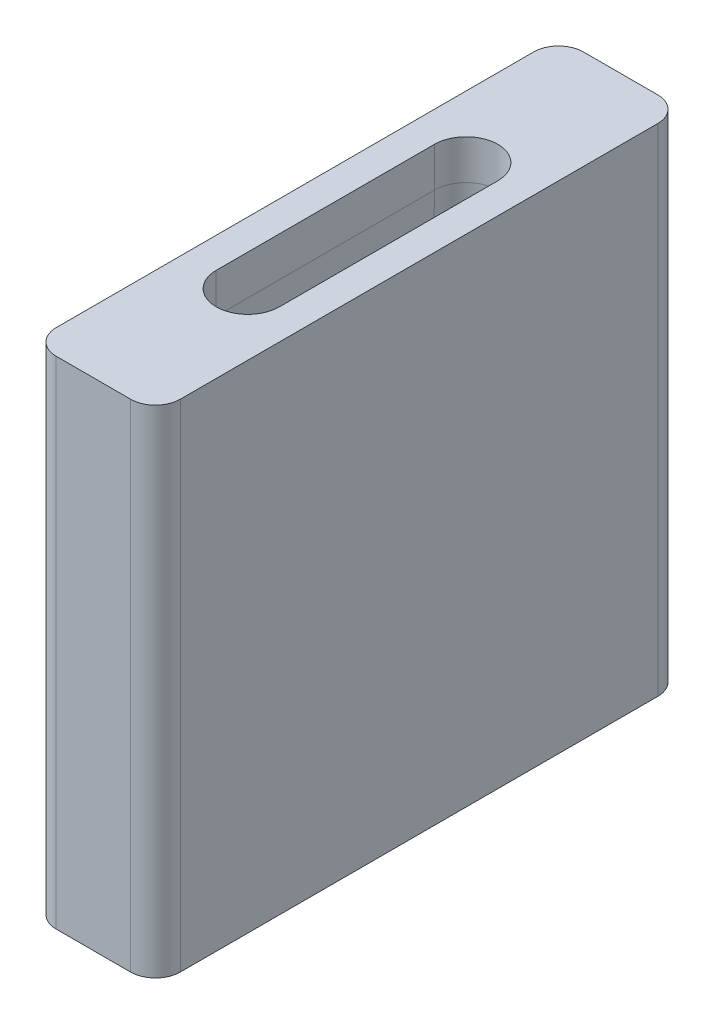
SolidWorks part; units mm, degrees
material "K110"
ref_plane "Front Plane" through (0, 0, 0) normal (0, 0, 1) x (1, 0, 0)
ref_plane "Top Plane" through (0, 0, 0) normal (0, 1, 0) x (1, 0, 0)
ref_plane "Right Plane" through (0, 0, 0) normal (1, 0, 0) x (0, 0, -1)
sketch "Sketch1" plane through (0, 0, 0) normal (0, 1, 0) x (1, 0, 0)
  line L3 (0, -8.75) -> (0, 8.75) construction
  line L4 (-2.62, -8.75) -> (-2.62, 8.75) construction
  line L5 (2.62, -8.75) -> (2.62, 8.75) construction
  line L6 (-3, -21.25) -> (3, -21.25)
  line L7 (-5, -19.25) -> (-5, 19.25)
  line L8 (-3, 21.25) -> (3, 21.25)
  line L9 (5, -19.25) -> (5, 19.25)
  line L10 (-5, -21.25) -> (5, 21.25) construction
  line L11 (-5, 21.25) -> (5, -21.25) construction
  arc A2 (-2.62, -8.75) -> (2.62, -8.75) centre (0, -8.75) ccw construction
  arc A3 (2.62, 8.75) -> (-2.62, 8.75) centre (0, 8.75) ccw construction
  arc A4 (-3, -21.25) -> (-5, -19.25) centre (-3, -19.25) cw
  arc A5 (3, -21.25) -> (5, -19.25) centre (3, -19.25) ccw
  arc A6 (3, 21.25) -> (5, 19.25) centre (3, 19.25) cw
  arc A7 (-5, 19.25) -> (-3, 21.25) centre (-3, 19.25) cw
  point P0 (0, 0)
  point P10 (0, 0)
  dimension "D1" = 17.5
  dimension "D3" = 2.62
  dimension "D5" = 2
  dimension "D2" = 42.5
  dimension "D4" = 10
extrude "Boss-Extrude1" add sketch "Sketch1" against normal blind 40
sketch "Sketch5" plane through (0, 0, 0) normal (0, 1, 0) x (1, 0, 0)
  line L0 (0, -8.8) -> (0, 8.8) construction
  line L1 (-2.55, -8.8) -> (-2.55, 8.8)
  line L2 (2.55, -8.8) -> (2.55, 8.8)
  arc A0 (-2.55, -8.8) -> (2.55, -8.8) centre (0, -8.8) ccw
  arc A1 (2.55, 8.8) -> (-2.55, 8.8) centre (0, 8.8) ccw
  point P4 (0, 0)
  dimension "D1" = 17.6
  dimension "D2" = 5.1
extrude "Cut-Extrude2" cut sketch "Sketch5" against normal up to next
sketch "Sketch7" plane through (0, 0, 0) normal (0, 0, 1) x (1, 0, 0)
  line L0 (2.55, -3.2) -> (3.1923, -40)
  line L1 (2.55, -40) -> (2.55, 0) construction
  line L2 (-3, -40) -> (3, -40) construction
  line L3 (3.1923, -40) -> (2.55, -40)
  line L4 (2.55, -40) -> (2.55, -3.2)
  line L5 (5, 0) -> (3, 0) construction
  dimension "D1" = 3.2
  dimension "D2" = 1
sketch "Sketch8" plane through (0, 0, 0) normal (0, 1, 0) x (1, 0, 0)
  line L0 (-2.55, 8.8) -> (-2.55, -8.8) construction
  line L1 (2.55, -8.8) -> (2.55, 8.8) construction
  line L2 (-2.55, 8.8) -> (-2.55, -8.8)
  line L3 (2.55, -8.8) -> (2.55, 8.8)
  arc A0 (2.55, 8.8) -> (-2.55, 8.8) centre (0, 8.8) ccw construction
  arc A1 (-2.55, -8.8) -> (2.55, -8.8) centre (0, -8.8) ccw construction
  arc A2 (2.55, 8.8) -> (-2.55, 8.8) centre (0, 8.8) ccw
  arc A3 (-2.55, -8.8) -> (2.55, -8.8) centre (0, -8.8) ccw
sweep "Cut-Sweep1" cut profiles "Sketch7" path "Sketch8"
hole_wizard "M6 Tapped Hole1" positions "Sketch11" profile "Sketch10" tap size "M6" standard "ISO"
sketch "Sketch11" plane through (0, -40, 0) normal (0, -1, 0) x (-1, 0, 0)
  line L0 (-3, 21.25) -> (3, 21.25) construction
  line L5 (3, -21.25) -> (-3, -21.25) construction
  line L6 (0, 21.25) -> (0, -21.25) construction
  point P0 (0, 16.25)
  point P2 (0, -16.25)
  dimension "D1" = 5
  dimension "D4" = 5
sketch "Sketch10" plane through (0, -40, -16.25) normal (1, 0, 0) x (0, 0, -1)
  line L0 (0, 0) -> (0, 18.5022)
  line L1 (0, 18.5022) -> (2.5, 17)
  line L2 (2.5, 17) -> (2.5, 0.525)
  line L3 (2.5, 0.525) -> (3.025, 0)
  line L5 (3.025, 0) -> (0, 0)
  line L6 (-2.5, 0.525) -> (-3.025, 0) construction
  line L10 (0, 18.5022) -> (-2.5, 17) construction
  line L11 (0, -6.35) -> (0, 107.95) construction
  dimension "Tap Drill Dia." = 5
  dimension "Tap Drill Depth" = 17
  dimension "Near C'Sink Dia." = 6.05
  dimension "Near C'Sink Angle" = 90
  dimension "Drill Angle" = 118
cosmetic thread "Hole Thread1"
cosmetic thread "Hole Thread2"
